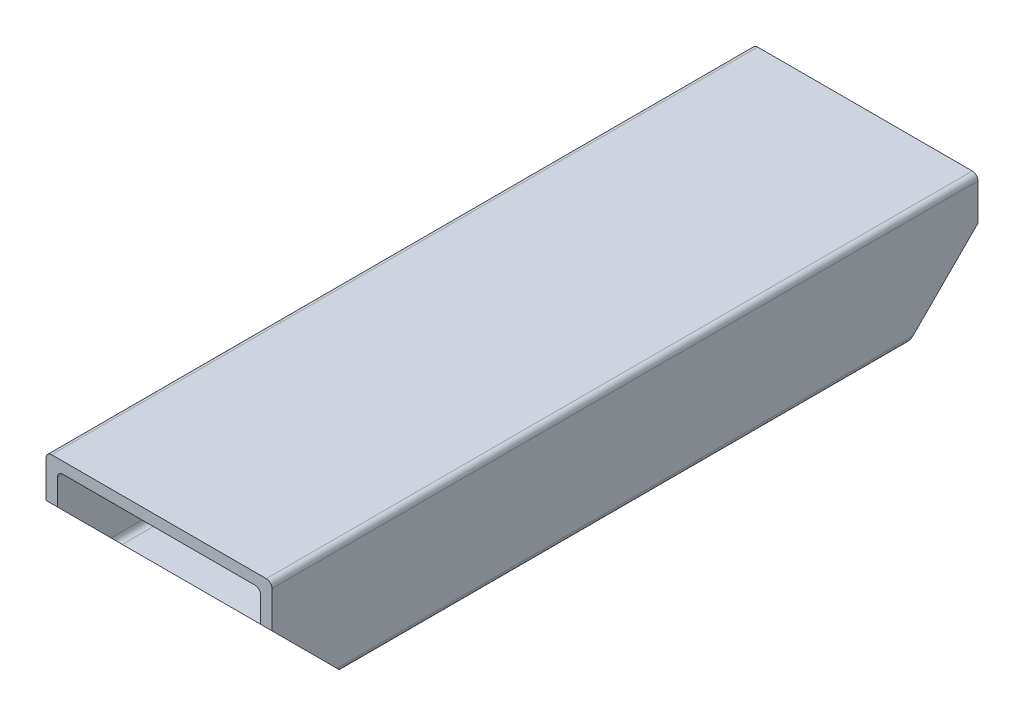
SolidWorks part; units mm, degrees
ref_plane "Plan de face" through (0, 0, 0) normal (0, 0, 1) x (1, 0, 0)
ref_plane "Plan de dessus" through (0, 0, 0) normal (0, 1, 0) x (1, 0, 0)
ref_plane "Plan de droite" through (0, 0, 0) normal (1, 0, 0) x (0, 0, -1)
sketch "Esquisse2" plane through (0, 0, 0) normal (0, 0, 1) x (1, 0, 0)
  line L0 (6, 4) -> (74, 4)
  line L1 (2, 0) -> (78, 0)
  line L2 (0, 2) -> (0, 38)
  line L3 (2, 40) -> (78, 40)
  line L4 (80, 2) -> (80, 38)
  line L5 (76, 6) -> (76, 34)
  line L6 (6, 36) -> (74, 36)
  line L7 (4, 6) -> (4, 34)
  line L8 (4, 4) -> (76, 4) construction
  line L9 (76, 4) -> (76, 36) construction
  line L10 (4, 36) -> (76, 36) construction
  line L11 (4, 4) -> (4, 36) construction
  line L12 (0, 0) -> (80, 0) construction
  line L13 (0, 0) -> (0, 40) construction
  line L14 (0, 40) -> (80, 40) construction
  line L15 (80, 0) -> (80, 40) construction
  arc A0 (74, 4) -> (76, 6) centre (74, 6) ccw
  arc A1 (76, 34) -> (74, 36) centre (74, 34) ccw
  arc A2 (6, 36) -> (4, 34) centre (6, 34) ccw
  arc A3 (4, 6) -> (6, 4) centre (6, 6) ccw
  arc A4 (2, 0) -> (0, 2) centre (2, 2) cw
  arc A5 (0, 38) -> (2, 40) centre (2, 38) cw
  arc A6 (78, 40) -> (80, 38) centre (78, 38) cw
  arc A7 (80, 2) -> (78, 0) centre (78, 2) cw
  point P24 (0, 0)
  dimension "D4" = 2
  dimension "D1" = 40
  dimension "D2" = 80
  dimension "D3" = 4
extrude "Boss.-Extru.1" add sketch "Esquisse2" along normal blind 250
sketch "Esquisse3" plane through (80, 0, 0) normal (1, 0, 0) x (0, 0, -1)
  line L0 (-125, 40) -> (-125, 0) construction
  line L1 (-250, 40) -> (0, 40) construction
  line L2 (0, 25) -> (-25, 0)
  line L3 (0, 2) -> (0, 38) construction
  line L5 (-25, 0) -> (0, 0)
  line L6 (0, 0) -> (0, 25)
  line L7 (-250, 0) -> (0, 0) construction
  line L8 (-250, 25) -> (-225, 0)
  line L9 (-250, 0) -> (-250, 25)
  line L10 (-225, 0) -> (-250, 0)
  dimension "D1" = 15
  dimension "D2" = 45
extrude "Enlèv. mat.-Extru.1" cut sketch "Esquisse3" against normal through all
